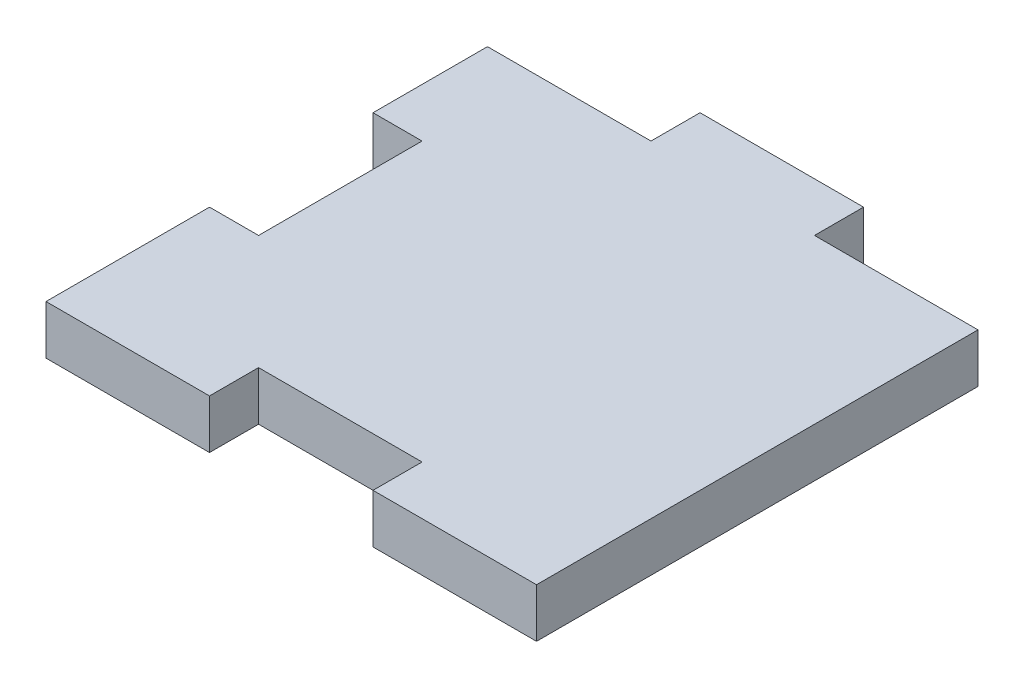
SolidWorks part; units mm, degrees
ref_plane "Alzado" through (0, 0, 0) normal (0, 0, 1) x (1, 0, 0)
ref_plane "Planta" through (0, 0, 0) normal (0, 1, 0) x (1, 0, 0)
ref_plane "Vista lateral" through (0, 0, 0) normal (1, 0, 0) x (0, 0, -1)
sketch "Croquis1" plane through (0, 0, 0) normal (0, 1, 0) x (1, 0, 0)
  line L0 (-50, -16.6667) -> (-50, -50)
  line L1 (-50, -50) -> (-16.6667, -50)
  line L2 (-16.6667, -50) -> (-16.6667, -40)
  line L3 (-16.6667, -40) -> (16.6667, -40)
  line L4 (16.6667, -40) -> (16.6667, -50)
  line L5 (16.6667, -50) -> (50, -50)
  line L6 (50, -50) -> (50, 40)
  line L7 (50, 40) -> (16.6667, 40)
  line L8 (16.6667, 40) -> (16.6667, 50)
  line L9 (16.6667, 50) -> (-16.6667, 50)
  line L10 (-16.6667, 50) -> (-16.6667, 40)
  line L11 (-16.6667, 40) -> (-50, 40)
  line L12 (-50, 40) -> (-50, 16.6667)
  line L13 (-50, 16.6667) -> (-40, 16.6667)
  line L14 (-40, 16.6667) -> (-40, -16.6667)
  line L15 (-40, -16.6667) -> (-50, -16.6667)
  point P3 (-40, 0)
  dimension "D1" = 40
  dimension "D2" = 10
  dimension "D3" = 50
  dimension "D4" = 50
  dimension "D5" = 100
extrude "Saliente-Extruir1" add sketch "Croquis1" along normal blind 10
